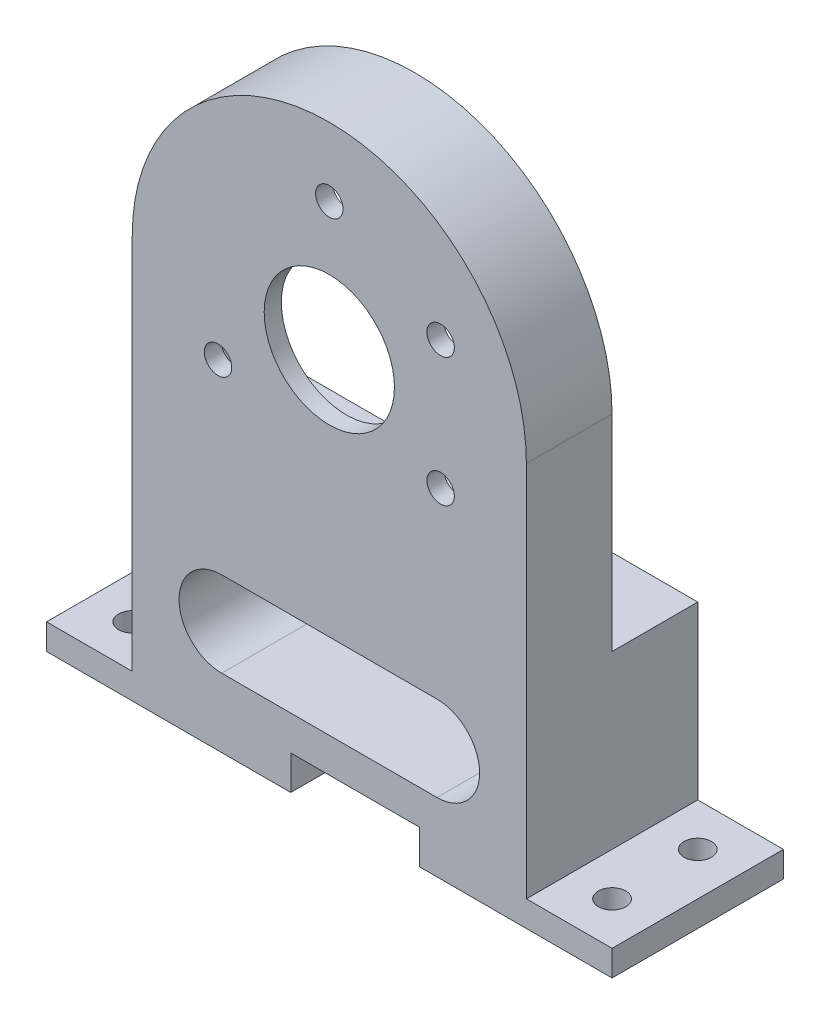
SolidWorks part; units mm, degrees
ref_plane "前视基准面" through (0, 0, 0) normal (0, 0, 1) x (1, 0, 0)
ref_plane "上视基准面" through (0, 0, 0) normal (0, 1, 0) x (1, 0, 0)
ref_plane "右视基准面" through (0, 0, 0) normal (1, 0, 0) x (0, 0, -1)
other "Configuration Table"
sketch "草图1" plane through (0, 0, 0) normal (0, 0, 1) x (1, 0, 0)
  line L0 (-23, 0) -> (-23, -27)
  line L1 (-23, -27) -> (23, -27)
  line L2 (23, -27) -> (23, 0)
  arc A1 (23, 0) -> (-23, 0) centre (0, 0) ccw
  dimension "D1" = 27
  dimension "D2" = 23
extrude "凸台-拉伸1" add sketch "草图1" along normal blind 20
sketch "草图2" plane through (0, 0, 0) normal (0, 0, -1) x (-1, 0, 0)
  line L0 (-23, -24) -> (23, -24)
  line L1 (23, 0) -> (23, -27) construction
  line L2 (-23, -27) -> (-23, 0) construction
  line L3 (-23, 0) -> (-23, -27)
  line L4 (-23, -27) -> (23, -27)
  line L5 (23, -27) -> (23, 0)
  line L6 (-23, 0) -> (-23, -24)
  line L8 (23, -24) -> (23, 0)
  arc A1 (23, 0) -> (-23, 0) centre (0, 0) ccw
  arc A2 (23, 0) -> (-23, 0) centre (0, 0) ccw
  dimension "D2" = 24
  dimension "D1" = 0
extrude "切除-拉伸1" cut sketch "草图2" against normal blind 10
sketch "草图3" plane through (0, 0, 10) normal (0, 0, -1) x (-1, 0, 0)
  circle A0 centre (0, 0) radius 21.1
  dimension "D1" = 42.2
extrude "切除-拉伸2" cut sketch "草图3" against normal blind 8
sketch "草图7" plane through (0, 0, 20) normal (0, 0, 1) x (1, 0, 0)
  circle A0 centre (0, 0) radius 15 construction
  circle A2 centre (0, 15) radius 1.6
  circle A4 centre (12.9904, 7.5) radius 1.6
  circle A5 centre (12.9904, -7.5) radius 1.6
  circle A8 centre (-12.9904, -7.5) radius 1.6
  point P10 (0, 0)
  dimension "D1" = 15
  dimension "D2" = 15
  dimension "D3" = 2
  dimension "D4" = 30
extrude "切除-拉伸6" cut sketch "草图7" against normal blind 3
sketch "草图8" plane through (0, 0, 18) normal (0, 0, -1) x (-1, 0, 0)
  circle A2 centre (0, 0) radius 7.6
  dimension "D1" = 15.2
extrude "切除-拉伸7" cut sketch "草图8" against normal blind 3
sketch "草图12" plane through (0, -27, 0) normal (0, -1, 0) x (1, 0, 0)
  line L4 (-23, 0) -> (23, 0)
  line L5 (23, 0) -> (23, 20)
  line L6 (23, 20) -> (-23, 20)
  line L7 (-23, 20) -> (-23, 0)
  line L8 (-23, 0) -> (23, 0)
  line L9 (23, 0) -> (23, 20)
  line L10 (23, 20) -> (-23, 20)
  line L11 (-23, 20) -> (-23, 0)
  dimension "D1" = 0
extrude "凸台-拉伸4" add sketch "草图12" along normal blind 20
sketch "草图14" plane through (0, -47, 0) normal (0, -1, 0) x (1, 0, 0)
  line L0 (23, 20) -> (33, 20)
  line L1 (-33, 20) -> (-23, 20)
  line L2 (-33, 20) -> (-33, 0)
  line L3 (-33, 0) -> (-23, 0)
  line L4 (33, 20) -> (33, 0)
  line L6 (-23, 20) -> (-23, 0)
  line L8 (23, 20) -> (23, 0)
  line L9 (23, 0) -> (33, 0)
  circle A0 centre (28, 5) radius 1.6
  circle A1 centre (28, 15) radius 1.6
  circle A2 centre (-28, 5) radius 1.6
  circle A3 centre (-28, 15) radius 1.6
  dimension "D3" = 3.2
  dimension "D1" = 3.2
  dimension "D2" = 3.2
  dimension "D4" = 3.2
extrude "凸台-拉伸5" add sketch "草图14" against normal blind 3
sketch "草图16" plane through (0, -47, 0) normal (0, -1, 0) x (1, 0, 0)
  line L6 (-33, 0) -> (33, 0) construction
  line L8 (-4.5, 0) -> (-4.5, 20)
  line L9 (-4.5, 20) -> (10.5, 20)
  line L10 (10.5, 0) -> (10.5, 20)
  line L13 (33, 20) -> (-33, 20) construction
  line L14 (-4.5, 0) -> (10.5, 0)
  point P0 (0, 0)
  dimension "D1" = 15
extrude "切除-拉伸10" cut sketch "草图16" against normal blind 4
sketch "草图17" plane through (0, 0, 0) normal (0, 0, -1) x (-1, 0, 0)
  line L0 (-23, -34) -> (23, -34) construction
  line L1 (0, -6.9725) -> (0, -46.4647) construction
  line L2 (-12.5662, -34) -> (12.5662, -34) construction
  line L3 (-12.5662, -29.0283) -> (12.5662, -29.0283)
  line L4 (-12.5662, -38.9717) -> (12.5662, -38.9717)
  arc A0 (-12.5662, -29.0283) -> (-12.5662, -38.9717) centre (-12.5662, -34) ccw
  arc A1 (12.5662, -38.9717) -> (12.5662, -29.0283) centre (12.5662, -34) ccw
  point P7 (0, -34)
extrude "切除-拉伸11" cut sketch "草图17" against normal through all
